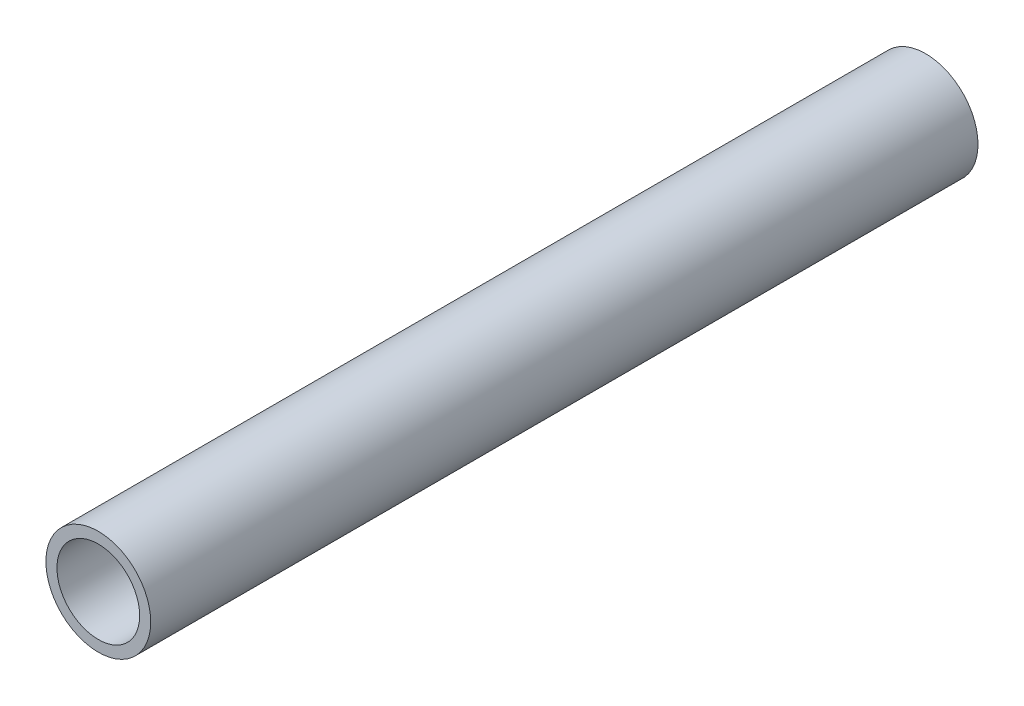
SolidWorks part; units mm, degrees
material "ﾎﾟﾘ塩化ﾋﾞﾆﾙ(PVC)硬質"
ref_plane "正面" through (0, 0, 0) normal (0, 0, 1) x (1, 0, 0)
ref_plane "平面" through (0, 0, 0) normal (0, 1, 0) x (1, 0, 0)
ref_plane "右側面" through (0, 0, 0) normal (1, 0, 0) x (0, 0, -1)
sketch "ｽｹｯﾁ1" plane through (0, 0, 0) normal (0, 0, 1) x (1, 0, 0)
  circle A0 centre (0, 0) radius 19
  circle A1 centre (0, 0) radius 15
  dimension "D1" = 30
  dimension "D2" = 38
extrude "ﾎﾞｽ - 押し出し1" add sketch "ｽｹｯﾁ1" along normal blind 300
